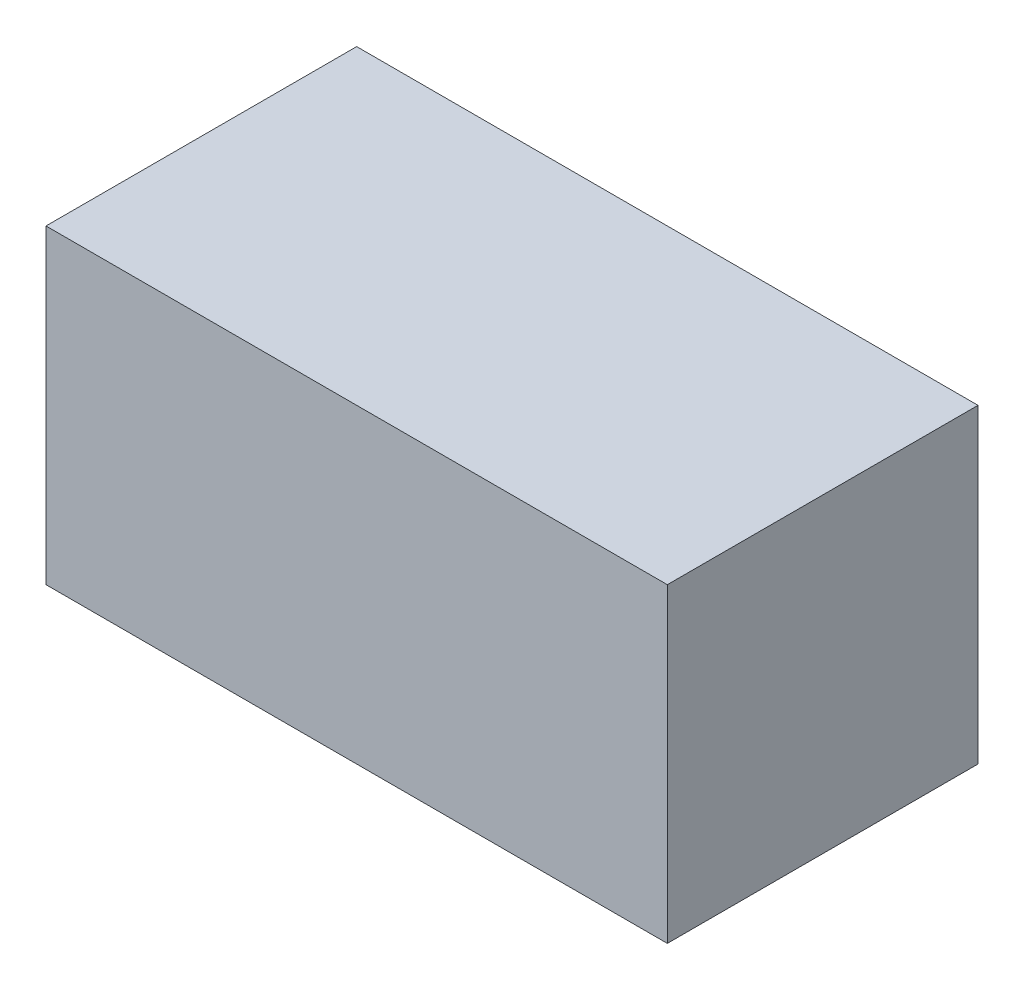
SolidWorks part; units mm, degrees
ref_plane "前视基准面" through (0, 0, 0) normal (0, 0, 1) x (1, 0, 0)
ref_plane "上视基准面" through (0, 0, 0) normal (0, 1, 0) x (1, 0, 0)
ref_plane "右视基准面" through (0, 0, 0) normal (1, 0, 0) x (0, 0, -1)
sketch "草图1" plane through (0, 0, 0) normal (0, 1, 0) x (1, 0, 0)
  line L1 (0, 0) -> (40, 0)
  line L2 (0, 0) -> (0, -20)
  line L3 (0, -20) -> (40, -20)
  line L4 (40, 0) -> (40, -20)
  dimension "D1" = 20
  dimension "D2" = 40
extrude "凸台-拉伸1" add sketch "草图1" along normal blind 20
